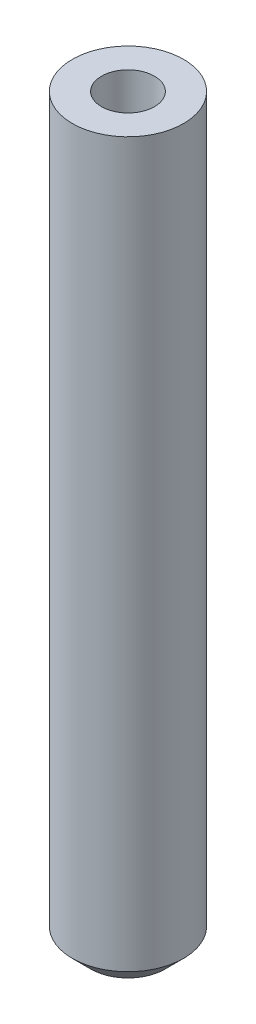
SolidWorks part; units mm, degrees
ref_plane "前视基准面" through (0, 0, 0) normal (0, 0, 1) x (1, 0, 0)
ref_plane "上视基准面" through (0, 0, 0) normal (0, 1, 0) x (1, 0, 0)
ref_plane "右视基准面" through (0, 0, 0) normal (1, 0, 0) x (0, 0, -1)
sketch "草图1" plane through (0, 0, 0) normal (0, 1, 0) x (1, 0, 0)
  circle A0 centre (0, 0) radius 3
  dimension "D1" = 6
extrude "凸台-拉伸1" add sketch "草图1" along normal blind 40
sketch "草图2" plane through (0, 0, 0) normal (0, -1, 0) x (1, 0, 0)
  circle A0 centre (0, 0) radius 1.4277
extrude "切除-拉伸1" cut sketch "草图2" against normal through all
chamfer "倒角1" distance 1 angle 45 1 edges at (0, 0, 3)
